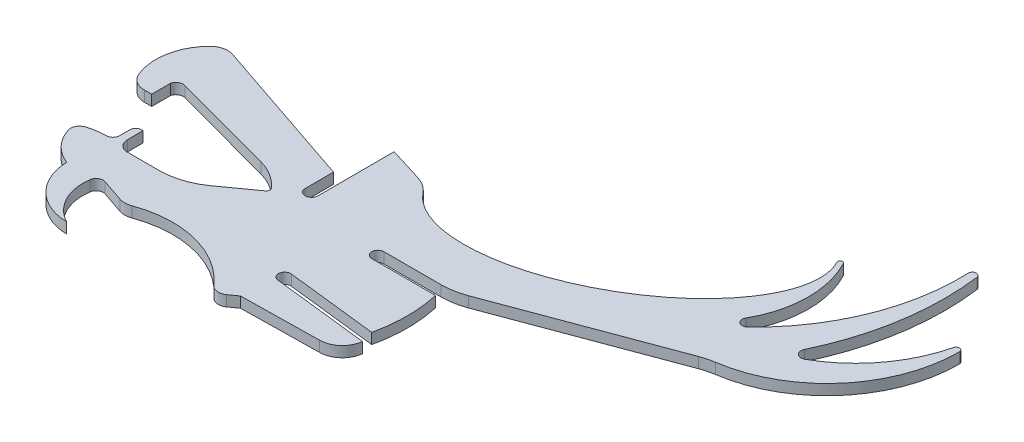
SolidWorks part; units mm, degrees
ref_plane "Front Plane" through (0, 0, 0) normal (0, 0, 1) x (1, 0, 0)
ref_plane "Top Plane" through (0, 0, 0) normal (0, 1, 0) x (1, 0, 0)
ref_plane "Right Plane" through (0, 0, 0) normal (1, 0, 0) x (0, 0, -1)
sketch "Sketch1" plane through (0, 0, 0) normal (0, 1, 0) x (1, 0, 0)
  line L0 (3.2405, 9.7011) -> (79.7861, 49.1654) construction
  line L1 (83.2776, 6.5774) -> (36.0632, -10.9968)
  line L2 (29.4353, -12.1903) -> (13.3316, -12.1903)
  line L3 (13.3316, -15.5903) -> (31.3356, -15.5903)
  line L4 (31.3356, -15.5903) -> (31.3356, -33.6115) construction
  line L5 (31.3356, -33.6115) -> (5.7182, -30.6928)
  line L6 (5.3333, -34.0709) -> (32.2588, -37.1387)
  line L7 (3.9316, -43.2347) -> (25.8383, -42.8691)
  line L8 (3.9316, -43.2347) -> (1.645, -44.8795)
  line L9 (-36.732, -36.5554) -> (-43.072, -34.4135)
  line L10 (-52.2665, -21.1248) -> (-52.2665, -18.2553)
  line L11 (-50.5665, -16.5553) -> (-50.185, -16.5553)
  line L12 (-50.185, -16.5553) -> (-50.185, -21.009)
  line L13 (-47.1388, -24.0553) -> (-38.2581, -24.0553)
  line L14 (-27.1635, -20.4796) -> (-18.2139, -14.0423)
  line L15 (-25.9633, -7.5659) -> (-55.3095, 0.3493)
  line L16 (-57.8833, -1.131) -> (-57.8833, -6.4672)
  line L17 (-57.8833, -6.4672) -> (-59.9704, -6.4672)
  line L18 (-56.2151, 14.68) -> (-13.214, 0.1522)
  line L21 (-9.6452, 13.6863) -> (3.2405, 9.7011)
  line L23 (-9.6452, 13.6863) -> (-9.5955, -7.8349)
  line L25 (-13.1955, -7.8433) -> (-13.214, 0.1522)
  arc A0 (79.7861, 49.1654) -> (80.9805, 49.7898) centre (80.3851, 49.4742) cw
  arc A1 (80.9805, 49.7898) -> (80.573, 22.6505) centre (56.0778, 36.591) cw
  arc A2 (80.573, 22.6505) -> (83.0608, 20.7057) centre (81.96, 21.8611) ccw
  arc A3 (83.0608, 20.7057) -> (100.9952, 64.9712) centre (43.0842, 62.6683) ccw
  arc A4 (100.9952, 64.9712) -> (103.2344, 65.1614) centre (102.1191, 65.0159) cw
  arc A5 (103.2344, 65.1614) -> (96.5249, 23.2653) centre (29.2943, 55.5173) cw
  arc A6 (96.5249, 23.2653) -> (99.0346, 20.917) centre (98.1492, 22.486) ccw
  arc A7 (99.0346, 20.917) -> (117.0982, 44.7424) centre (80.5346, 53.7034) ccw
  arc A8 (117.0982, 44.7424) -> (118.9683, 44.5166) centre (118.0196, 44.5166) cw
  arc A10 (118.9683, 44.5166) -> (87.1085, 7.5639) centre (81.6086, 44.5166) cw
  arc A11 (13.3316, -12.1903) -> (13.3316, -15.5903) centre (13.3316, -13.8903) ccw
  arc A12 (5.7182, -30.6928) -> (5.3333, -34.0709) centre (5.5257, -32.3818) ccw
  arc A13 (32.2588, -37.1387) -> (25.8383, -42.8691) centre (25.8383, -36.4072) cw
  arc A14 (-2.3631, -44.4212) -> (-33.4065, -36.5114) centre (-23.644, -63.0694) ccw
  arc A15 (-45.691, -36.0178) -> (-38.702, -49.6317) centre (-32.6625, -37.9303) ccw
  arc A16 (-38.702, -49.6317) -> (-53.199, -35.0885) centre (-38.4397, -34.8731) cw
  arc A17 (-53.199, -35.0885) -> (-60.8804, -27.0039) centre (-48.6613, -23.0856) cw
  arc A18 (-60.8804, -27.0039) -> (-59.2327, -23.8007) centre (-58.455, -26.2262) cw
  arc A19 (-59.2327, -23.8007) -> (-54.147, -23.0053) centre (-54.147, -39.6606) cw
  arc A20 (-54.147, -23.0053) -> (-52.2665, -21.1248) centre (-54.147, -21.1248) ccw
  arc A21 (-50.185, -21.009) -> (-47.1388, -24.0553) centre (-47.1388, -21.009) ccw
  arc A22 (-18.2139, -14.0423) -> (-18.0368, -12.5767) centre (-18.7996, -13.228) ccw
  arc A23 (-18.0368, -12.5767) -> (-25.9633, -7.5659) centre (-30.0913, -22.8707) ccw
  arc A24 (-55.3095, 0.3493) -> (-57.8833, -1.131) centre (-55.8563, -1.6778) ccw
  arc A25 (-64.5871, -3.3871) -> (-61.414, 13.4145) centre (-50.1997, 2.5961) cw
  arc A27 (-61.414, 13.4145) -> (-56.2151, 14.68) centre (-57.8155, 9.9431) cw
  arc A28 (-33.4065, -36.5114) -> (-36.732, -36.5554) centre (-35.1317, -31.8184) cw
  arc A29 (1.645, -44.8795) -> (-2.3631, -44.4212) centre (-0.1068, -42.444) cw
  arc A30 (-43.072, -34.4135) -> (-45.691, -36.0178) centre (-43.7122, -36.3083) ccw
  arc A31 (-52.2665, -18.2553) -> (-50.5665, -16.5553) centre (-50.5665, -18.2553) cw
  arc A32 (-59.9704, -6.4672) -> (-64.5871, -3.3871) centre (-59.9704, -1.4672) cw
  arc A33 (31.3356, -15.5903) -> (31.3356, -33.6115) centre (-9.027, -24.6009) cw
  arc A34 (-38.2581, -24.0553) -> (-27.1635, -20.4796) centre (-38.2581, -5.0553) ccw
  arc A35 (36.0632, -10.9968) -> (29.4353, -12.1903) centre (29.4353, 6.8097) cw
  arc A36 (87.1085, 7.5639) -> (83.2776, 6.5774) centre (89.9056, -11.2291) ccw
  arc A37 (-13.1955, -7.8433) -> (-9.5955, -7.8349) centre (-11.3955, -7.8391) ccw
  ellipse E0 centre (41.5133, 29.4332) end of major axis (3.2405, 9.7011) minor radius 23.25 (3.2405, 9.7011) -> (79.7861, 49.1654) ccw
  ellipse E1 centre (-10.1584, 5.4338) end of major axis (-10.1354, -4.5662) minor radius 1.1584 (-9.1015, 1.1587) -> (-9.0314, 7.5629) ccw construction
  ellipse E2 centre (-10.1584, 5.4338) end of major axis (-10.1354, -4.5662) minor radius 1.1584 (-9.0001, 5.4365) -> (-9.0314, 7.5629) ccw construction
  point P75 (0, 0)
  point P82 (-32.1346, -24.0553)
  point P85 (32.8567, -12.1903)
  point P88 (85.3349, 7.3432)
  point P96 (0, 0)
  point P100 (0, 0)
  point P102 (-10.7066, 13.4145)
  point P106 (-58.8363, 15.5656)
  point P109 (-34.9843, -37.1459)
  point P112 (-0.6734, -46.5471)
  point P115 (-45.1378, -33.7155)
  point P120 (-62.8746, -6.4672)
  dimension "D9" = 0.6739
  dimension "D10" = 28.1843
  dimension "D11" = 1.5959
  dimension "D12" = 57.9568
  dimension "D13" = 1.1247
  dimension "D14" = 74.5664
  dimension "D15" = 1.8016
  dimension "D16" = 37.6456
  dimension "D17" = 0.9487
  dimension "D18" = 37.3597
  dimension "D19" = 6.462
  dimension "D20" = 28.2955
  dimension "D21" = 13.168
  dimension "D22" = 14.7609
  dimension "D23" = 12.832
  dimension "D24" = 2.5471
  dimension "D25" = 16.6553
  dimension "D26" = 1.8805
  dimension "D27" = 3.0463
  dimension "D28" = 1.003
  dimension "D29" = 15.8517
  dimension "D30" = 2.0995
  dimension "D31" = 15.5819
  dimension "D60" = 5
  dimension "D61" = 5
  dimension "D62" = 3
  dimension "D63" = 2
  dimension "D64" = 1.7
  dimension "D65" = 5
  dimension "D68" = 19
  dimension "D69" = 19
  dimension "D70" = 19
  dimension "D72" = 1.7
  dimension "D73" = 1.8
  dimension "D1" = 46.5
  dimension "D2" = 6.5
  dimension "86.12" = 86.12
  dimension "D5" = 102.71
  dimension "D7" = 6.45
  dimension "D8" = 7.5
  dimension "D32" = 3.2405
  dimension "D33" = 3.9316
  dimension "D34" = 5.3333
  dimension "D35" = 25.8383
  dimension "D36" = 29.2943
  dimension "D37" = 13.3316
  dimension "D38" = 30.859
  dimension "D39" = 43.0842
  dimension "D40" = 56.0778
  dimension "D41" = 31.3356
  dimension "D42" = 80.5346
  dimension "D43" = 32.8567
  dimension "D44" = 80.573
  dimension "D45" = 81.6086
  dimension "D46" = 96.5249
  dimension "D47" = 100.9952
  dimension "D48" = 0.6734
  dimension "D49" = 18.0368
  dimension "D50" = 18.2139
  dimension "D51" = 18.7996
  dimension "D52" = 25.9633
  dimension "D53" = 48.6613
  dimension "D54" = 52.2665
  dimension "D55" = 55.3095
  dimension "D56" = 85.3349
  dimension "D57" = 58.455
  dimension "D58" = 0.3493
  dimension "D59" = 2.5961
  dimension "D66" = 9.027
  dimension "D67" = 3.9853
  dimension "D71" = 48.2
  dimension "D74" = 32.1346
  dimension "D75" = 32.6625
  dimension "D76" = 34.9843
  dimension "D77" = 38.4397
  dimension "D78" = 38.702
  dimension "D79" = 45.1378
  dimension "D80" = 7.9913
  dimension "D81" = 50.185
  dimension "D82" = 50.1997
  dimension "D83" = 12.8857
  dimension "D84" = 53.199
  dimension "D85" = 1.8184
  dimension "D87" = 57.8833
  dimension "D89" = 58.8363
  dimension "D92" = 62.8746
  dimension "D102" = 13.8903
extrude "Boss-Extrude2" add sketch "Sketch1" along normal blind 3
fillet "Fillet1" radius 10 1 edges at (3.2405, 1.5, -9.7011)
